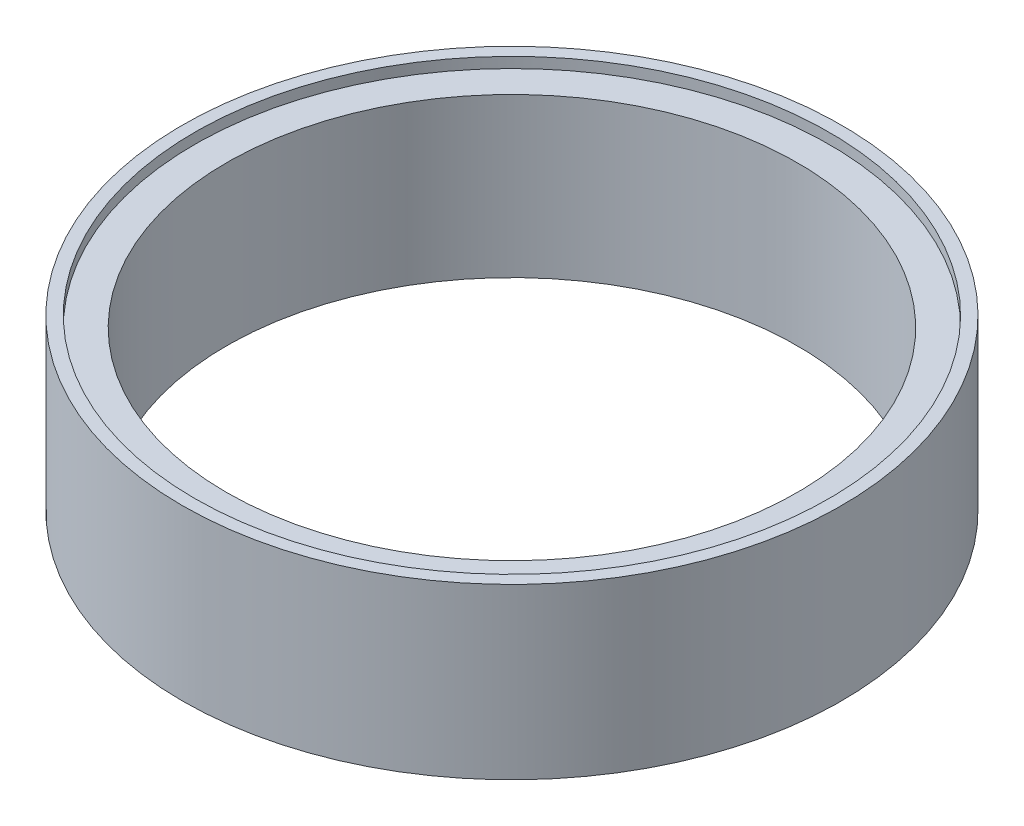
SolidWorks part; units mm, degrees
ref_plane "Front Plane" through (0, 0, 0) normal (0, 0, 1) x (1, 0, 0)
ref_plane "Top Plane" through (0, 0, 0) normal (0, 1, 0) x (1, 0, 0)
ref_plane "Right Plane" through (0, 0, 0) normal (1, 0, 0) x (0, 0, -1)
sketch "Sketch1" plane through (0, 0, 0) normal (0, 1, 0) x (1, 0, 0)
  circle A0 centre (0, 0) radius 9.35
  dimension "D1" = 18.7
extrude "Boss-Extrude1" add sketch "Sketch1" along normal blind 4.8
sketch "Sketch2" plane through (0, 4.8, 0) normal (0, 1, 0) x (1, 0, 0)
  circle A0 centre (0, 0) radius 8.1
  dimension "D1" = 16.2
extrude "Cut-Extrude1" cut sketch "Sketch2" against normal through all both and the other way through all
sketch "Sketch3" plane through (0, 4.8, 0) normal (0, 1, 0) x (1, 0, 0)
  circle A0 centre (0, 0) radius 9
  dimension "D1" = 18
extrude "Cut-Extrude2" cut sketch "Sketch3" against normal blind 0.3
